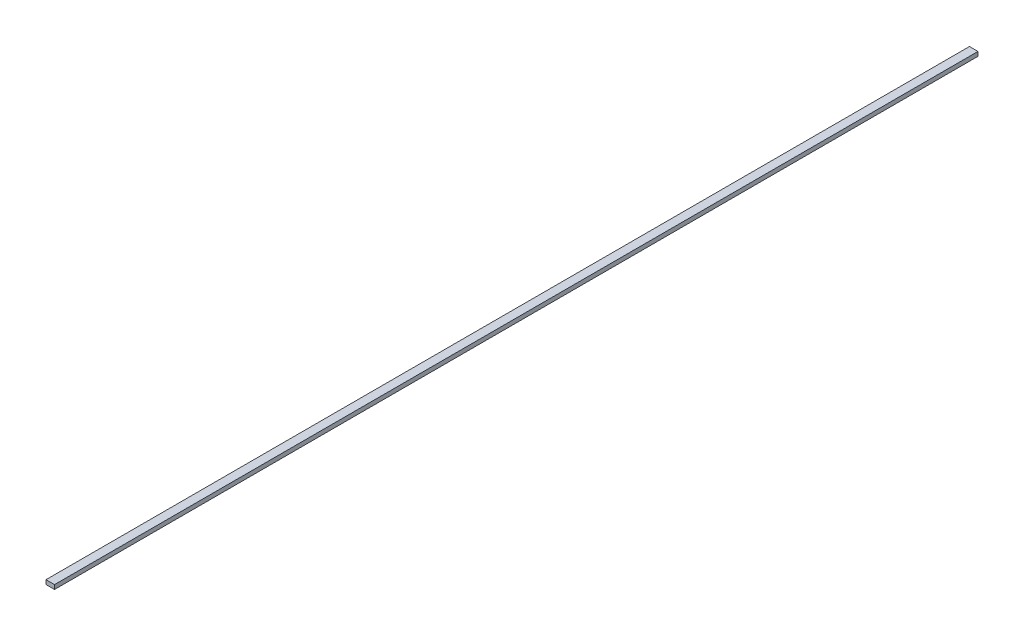
SolidWorks part; units mm, degrees
ref_plane "Front Plane" through (0, 0, 0) normal (0, 0, 1) x (1, 0, 0)
ref_plane "Top Plane" through (0, 0, 0) normal (0, 1, 0) x (1, 0, 0)
ref_plane "Right Plane" through (0, 0, 0) normal (1, 0, 0) x (0, 0, -1)
other "Configuration Table"
sketch "Sketch1" plane through (0, 0, 0) normal (0, 0, 1) x (1, 0, 0)
  line L1 (717, 1550) -> (723, 1550)
  line L2 (717, 1550) -> (717, 1553)
  line L3 (717, 1553) -> (723, 1553)
  line L4 (723, 1550) -> (723, 1553)
extrude "DET2_kayis_GT3_6mm_1" add sketch "Sketch1" against normal blind 650 from offset 40 separate body
